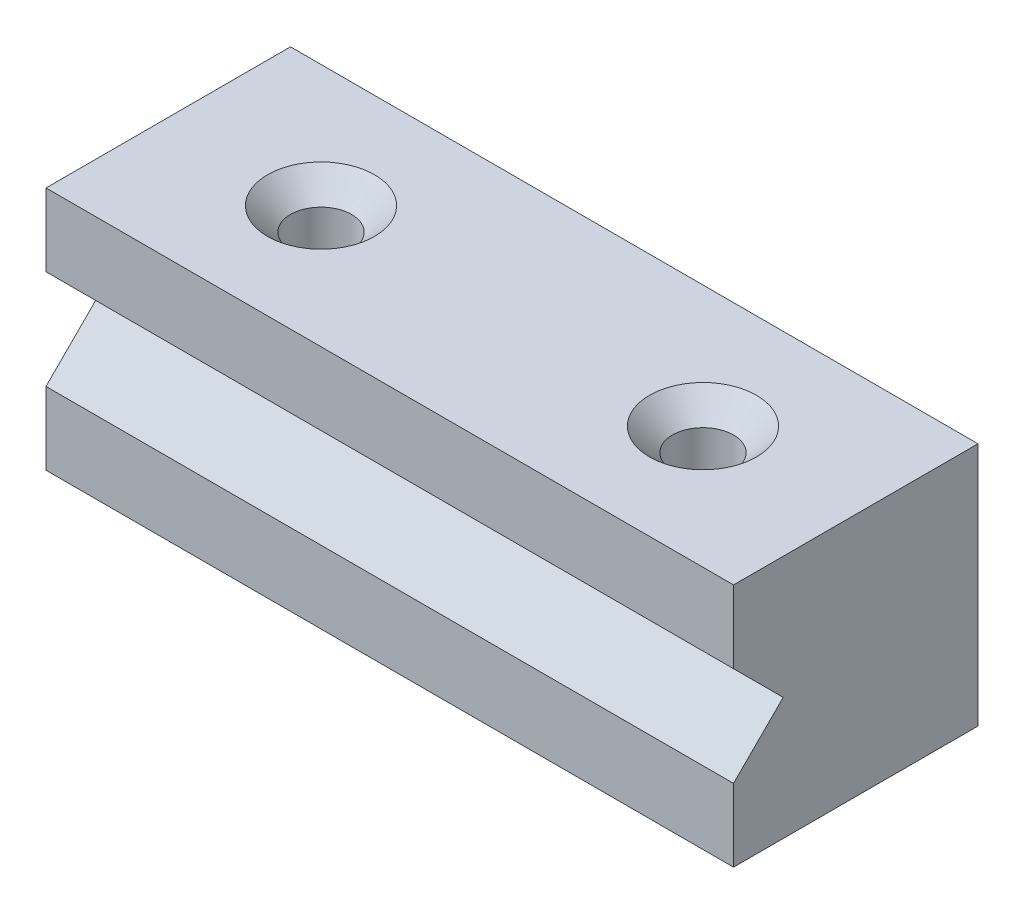
SolidWorks part; units mm, degrees
material "Chrome Stainless Steel"
ref_plane "Front Plane" through (0, 0, 0) normal (0, 0, 1) x (1, 0, 0)
ref_plane "Top Plane" through (0, 0, 0) normal (0, 1, 0) x (1, 0, 0)
ref_plane "Right Plane" through (0, 0, 0) normal (1, 0, 0) x (0, 0, -1)
sketch "Sketch1" plane through (0, 0, 0) normal (1, 0, 0) x (0, 0, -1)
  line L0 (-16, 6.5) -> (-9.5, 0)
  line L1 (-16, 16) -> (16, 16)
  line L2 (-16, 16) -> (-16, -16)
  line L3 (-16, -16) -> (16, -16)
  line L4 (16, 16) -> (16, -16)
  line L5 (-16, 16) -> (16, -16) construction
  line L6 (-16, -16) -> (16, 16) construction
  line L7 (-9.5, 0) -> (-16, -6.5)
  point P0 (0, 0)
  dimension "D1" = 32
  dimension "D2" = 32
  dimension "D3" = 13
  dimension "D4" = 90
  dimension "D5" = 6.5
extrude "Boss-Extrude1" add sketch "Sketch1" along normal mid plane 90 contours L0 L7 L2 L3 L4 L1
hole_wizard "Ø1.0mm Dowel Hole1" positions "Sketch2" profile "Sketch3" hole size "Ø1.0" standard "ANSI Metric" end condition up to next
sketch "Sketch2" plane through (0, 16, 0) normal (0, 1, 0) x (1, 0, 0)
  line L0 (45, -16) -> (45, 16) construction
  point P0 (25, 0)
  point P2 (-25, 0)
  dimension "D1" = 50
  dimension "D2" = 20
sketch "Sketch3" plane through (25, 16, 0) normal (1, 0, 0) x (0, 0, 1)
  line L0 (0, 0) -> (0, 32)
  line L1 (0, 32) -> (4, 32)
  line L2 (4, 32) -> (4, 0)
  line L5 (4, 0) -> (0, 0)
  line L11 (0, -6.35) -> (0, 107.95) construction
  dimension "Thru Hole Dia." = 8
  dimension "Thru Hole Depth" = 32
chamfer "Chamfer1" distance 3 angle 45 2 edges at (-25, 16, 4) (25, 16, 4)
